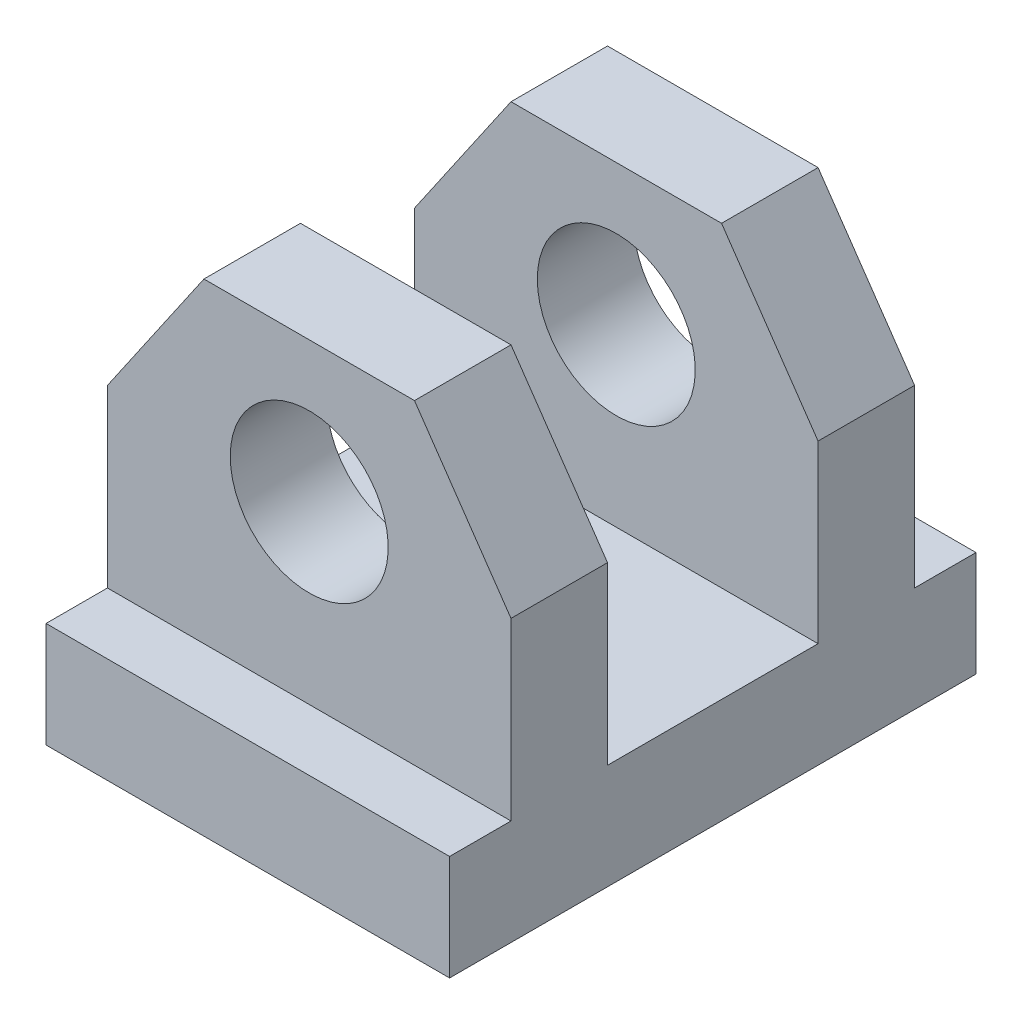
SolidWorks part; units mm, degrees
ref_plane "Alzado" through (0, 0, 0) normal (0, 0, 1) x (1, 0, 0)
ref_plane "Planta" through (0, 0, 0) normal (0, 1, 0) x (1, 0, 0)
ref_plane "Vista lateral" through (0, 0, 0) normal (1, 0, 0) x (0, 0, -1)
sketch "Croquis2" plane through (0, 0, 0) normal (0, 0, 1) x (1, 0, 0)
  line L0 (-23, 0) -> (23, 0)
  line L1 (23, 0) -> (23, 32)
  line L2 (23, 32) -> (12, 48)
  line L3 (12, 48) -> (-12, 48)
  line L4 (-12, 48) -> (-23, 32)
  line L5 (-23, 32) -> (-23, 0)
  circle A0 centre (0, 32) radius 9
  point P4 (0, 0)
  point P23 (0, 48)
  dimension "D4" = 18
  dimension "D1" = 32
  dimension "D2" = 48
  dimension "D3" = 46
  dimension "D5" = 24
extrude "Saliente-Extruir2" add sketch "Croquis2" along normal blind 60
sketch "Croquis3" plane through (0, 48, 0) normal (0, 1, 0) x (1, 0, 0)
  line L0 (23, -60) -> (23, 0) construction
  line L1 (-23, 0) -> (23, 0)
  line L2 (-23, 0) -> (-23, -7)
  line L3 (-23, -7) -> (23, -7)
  line L4 (23, 0) -> (23, -7)
  line L5 (12, -60) -> (-12, -60) construction
  line L6 (-23, -60) -> (23, -60)
  line L7 (-23, -60) -> (-23, -53)
  line L8 (-23, -53) -> (23, -53)
  line L9 (23, -60) -> (23, -53)
  line L10 (-23, -60) -> (-23, 0) construction
  dimension "D1" = 7
extrude "Cortar-Extruir2" cut sketch "Croquis3" against normal blind 36
sketch "Croquis4" plane through (0, 48, 0) normal (0, 1, 0) x (1, 0, 0)
  line L0 (-23, -53) -> (-23, -7) construction
  line L5 (-23, -18) -> (40.6729, -18)
  line L22 (23, -53) -> (23, -7) construction
  line L23 (-23, -18) -> (-23, -42)
  line L24 (-23, -42) -> (40.6729, -42)
  line L25 (40.6729, -18) -> (40.6729, -42)
  point P1 (23, -30)
  point P7 (-23, -30)
  point P10 (-23, -30)
extrude "Cortar-Extruir3" cut sketch "Croquis4" against normal blind 36
